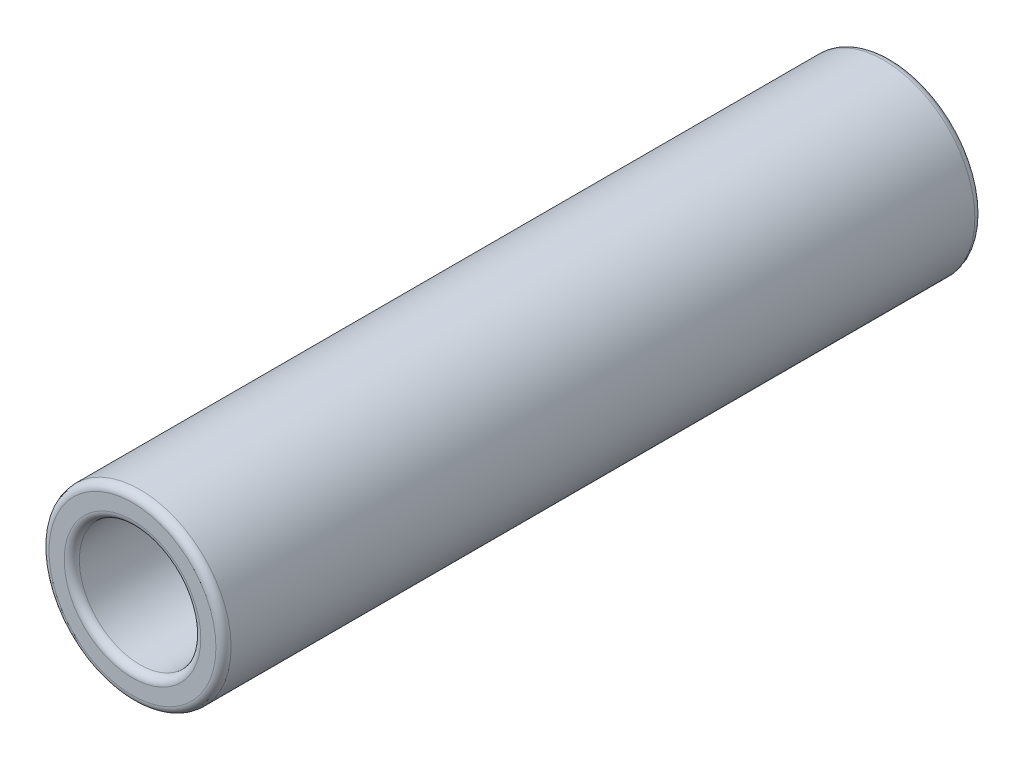
SolidWorks part; units mm, degrees
ref_plane "Front Plane" through (0, 0, 0) normal (0, 0, 1) x (1, 0, 0)
ref_plane "Top Plane" through (0, 0, 0) normal (0, 1, 0) x (1, 0, 0)
ref_plane "Right Plane" through (0, 0, 0) normal (1, 0, 0) x (0, 0, -1)
sketch "Sketch1" plane through (0, 0, 0) normal (0, 0, 1) x (1, 0, 0)
  circle A0 centre (0, 0) radius 4
  circle A1 centre (0, 0) radius 6
  dimension "D1" = 8
  dimension "D2" = 12
extrude "Boss-Extrude1" add sketch "Sketch1" along normal mid plane 50
fillet "Fillet1" radius 0.5 4 edges at (4, 0, -25) (4, 0, 25) (6, 0, -25) (6, 0, 25)
